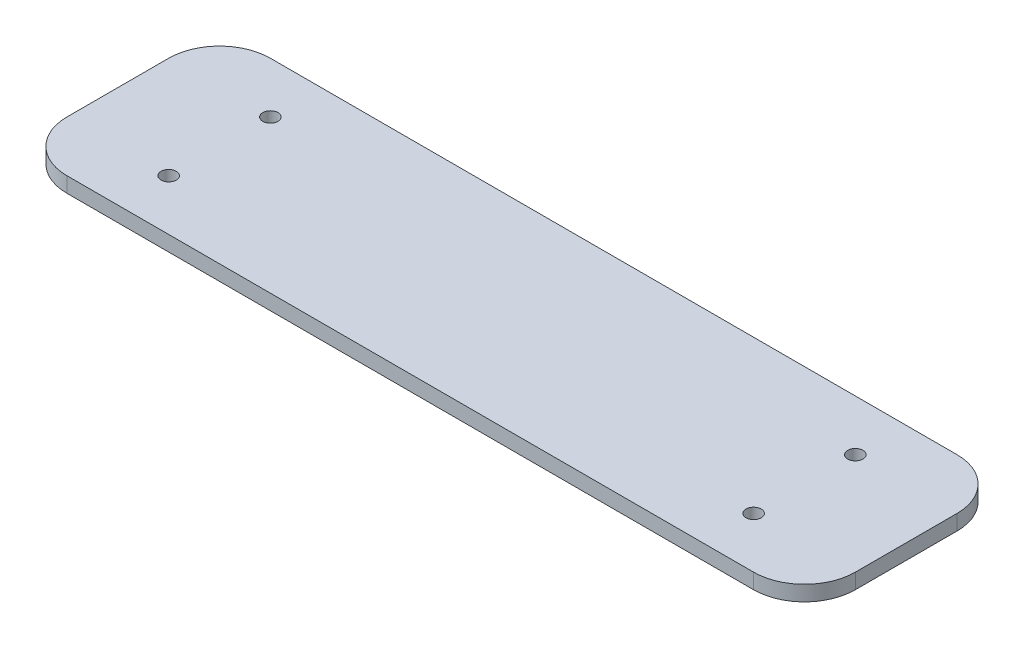
SolidWorks part; units mm, degrees
ref_plane "前基準面" through (0, 0, 0) normal (0, 0, 1) x (1, 0, 0)
ref_plane "上基準面" through (0, 0, 0) normal (0, 1, 0) x (1, 0, 0)
ref_plane "右基準面" through (0, 0, 0) normal (1, 0, 0) x (0, 0, -1)
sketch "草圖1" plane through (0, 0, 0) normal (0, 1, 0) x (1, 0, 0)
  line L1 (-77.5, 20) -> (77.5, 20)
  line L2 (-77.5, 20) -> (-77.5, -20)
  line L3 (-77.5, -20) -> (77.5, -20)
  line L4 (77.5, 20) -> (77.5, -20)
  line L5 (-77.5, 20) -> (77.5, -20) construction
  line L6 (-77.5, -20) -> (77.5, 20) construction
  line L7 (-57.5, 10) -> (57.5, 10) construction
  line L8 (-57.5, 10) -> (-57.5, -10) construction
  line L9 (-57.5, -10) -> (57.5, -10) construction
  line L10 (57.5, 10) -> (57.5, -10) construction
  circle A4 centre (-57.5, 10) radius 1.5
  circle A5 centre (-57.5, -10) radius 1.5
  circle A6 centre (57.5, -10) radius 1.5
  circle A7 centre (57.5, 10) radius 1.5
  point P0 (0, 0)
  point P10 (0, 10)
  point P15 (-57.5, 0)
  dimension "D3" = 20
  dimension "D6" = 3
  dimension "D1" = 155
  dimension "D2" = 40
  dimension "D4" = 115
extrude "填料-伸長1" add sketch "草圖1" along normal blind 3
fillet "圓角1" radius 10 4 edges at (-77.5, 1.5, 20) (77.5, 1.5, 20) (77.5, 1.5, -20) (-77.5, 1.5, -20)
